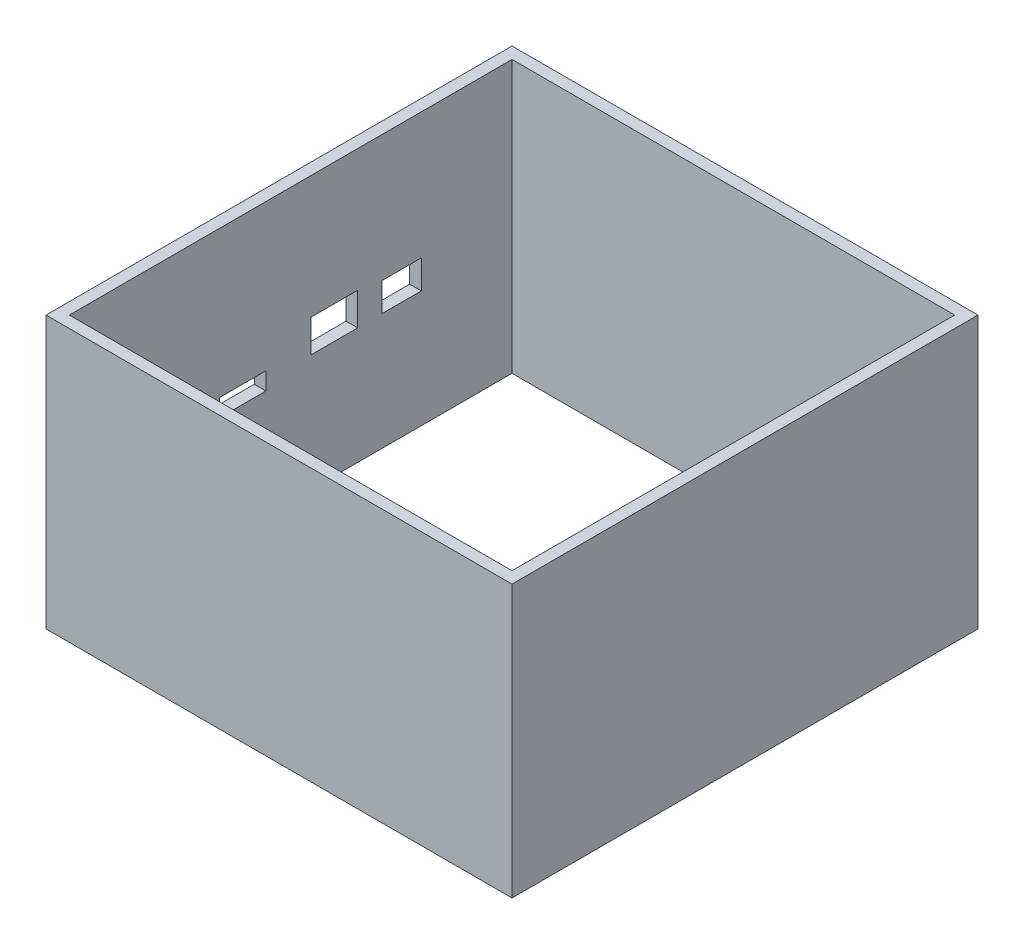
SolidWorks part; units mm, degrees
ref_plane "Front Plane" through (0, 0, 0) normal (0, 0, 1) x (1, 0, 0)
ref_plane "Top Plane" through (0, 0, 0) normal (0, 1, 0) x (1, 0, 0)
ref_plane "Right Plane" through (0, 0, 0) normal (1, 0, 0) x (0, 0, -1)
sketch "Sketch1" plane through (0, 0, 0) normal (0, 1, 0) x (1, 0, 0)
  line L1 (-70, -80) -> (70, -80)
  line L2 (-70, -80) -> (-70, 80)
  line L3 (-70, 80) -> (70, 80)
  line L4 (70, -80) -> (70, 80)
  line L5 (-70, -80) -> (70, 80) construction
  line L6 (-70, 80) -> (70, -80) construction
  point P0 (0, 0)
  dimension "D1" = 140
  dimension "D2" = 160
extrude "Boss-Extrude1" add sketch "Sketch1" along normal blind 3
sketch "Sketch2" plane through (0, 3, 0) normal (0, 1, 0) x (1, 0, 0)
  line L1 (-57, -57) -> (57, -57)
  line L2 (-57, -57) -> (-57, 57)
  line L3 (-57, 57) -> (57, 57)
  line L4 (57, -57) -> (57, 57)
  line L5 (-57, -57) -> (57, 57) construction
  line L6 (-57, 57) -> (57, -57) construction
  line L7 (60, -60) -> (-60, -60)
  line L8 (60, -60) -> (60, 60)
  line L9 (60, 60) -> (-60, 60)
  line L10 (-60, -60) -> (-60, 60)
  line L11 (60, -60) -> (-60, 60) construction
  line L12 (60, 60) -> (-60, -60) construction
  point P0 (0, 0)
  point P6 (0, 0)
  dimension "D1" = 114
  dimension "D2" = 114
  dimension "D3" = 120
extrude "Boss-Extrude2" add sketch "Sketch2" along normal blind 70
sketch "Sketch4" plane through (0, 73, 0) normal (0, 1, 0) x (1, 0, 0)
  line L1 (-60, 60) -> (60, 60)
  line L2 (-60, 60) -> (-60, -60)
  line L3 (-60, -60) -> (60, -60)
  line L4 (60, 60) -> (60, -60)
  dimension "D1" = 120
  dimension "D2" = 120
extrude "Boss-Extrude4" add sketch "Sketch4" along normal blind 3
sketch "Sketch5" plane through (0, 76, 0) normal (0, 1, 0) x (1, 0, 0)
  line L0 (-60, 60) -> (60, -60) construction
  line L1 (-10.27, -9.855) -> (29.63, -9.855)
  line L2 (-10.27, -9.855) -> (-10.27, 9.855)
  line L3 (-10.27, 9.855) -> (29.63, 9.855)
  line L4 (29.63, -9.855) -> (29.63, 9.855)
  line L5 (-10.27, -9.855) -> (29.63, 9.855) construction
  line L6 (-10.27, 9.855) -> (29.63, -9.855) construction
  line L7 (60, -60) -> (60, 60) construction
  line L8 (60, -60) -> (60, 60) construction
  line L9 (60, -60) -> (60, 60) construction
  line L10 (60, 60) -> (-60, 60) construction
  line L11 (60, 60) -> (-60, -60) construction
  circle A1 centre (34.39, -4.925) radius 2.1
  circle A2 centre (34.39, 4.925) radius 2.1
  circle A4 centre (-15.03, -4.925) radius 2.1
  circle A5 centre (-15.03, 4.925) radius 2.1
  point P3 (9.68, 0)
  dimension "D2" = 4.2
  dimension "D6" = 9.85
  dimension "D7" = 4.93
  dimension "D8" = 4.93
  dimension "D9" = 4.93
  dimension "D10" = 9.68
  dimension "D11" = 4.93
  dimension "D12" = 4.93
  dimension "D1" = 39.9
  dimension "D3" = 19.71
  dimension "D4" = 4.76
  dimension "D5" = 4.76
extrude "Cut-Extrude2" cut sketch "Sketch5" against normal blind 3
sketch "Sketch6" plane through (0, 76, 0) normal (0, 1, 0) x (1, 0, 0)
  line L1 (9.1491, -8.655) -> (-9.1491, -8.655)
  line L2 (9.1491, -8.655) -> (9.1491, 8.655)
  line L3 (9.1491, 8.655) -> (-9.1491, 8.655)
  line L4 (-9.1491, -8.655) -> (-9.1491, 8.655)
  line L5 (9.1491, -8.655) -> (-9.1491, 8.655) construction
  line L6 (9.1491, 8.655) -> (-9.1491, -8.655) construction
  point P0 (0, 0)
extrude "Cut-Extrude3" cut sketch "Sketch6" against normal blind 3
sketch "Sketch7" plane through (0, 0, 0) normal (0, 1, 0) x (1, 0, 0)
  line L1 (-45, -45) -> (45, -45)
  line L2 (-45, -45) -> (-45, 45)
  line L3 (-45, 45) -> (45, 45)
  line L4 (45, -45) -> (45, 45)
  line L5 (-45, -45) -> (45, 45) construction
  line L6 (-45, 45) -> (45, -45) construction
  point P0 (0, 0)
  dimension "D1" = 90
  dimension "D2" = 90
sketch "Sketch13" plane through (0, 76, 0) normal (0, 1, 0) x (1, 0, 0)
  arc A0 (-3.7926, 43.0768) -> (-0.8101, -42.9734) centre (-3.7926, 0) ccw construction
  arc A1 (-3.7926, 49.7288) -> (-0.3495, -49.6094) centre (-3.7926, 0) ccw
  arc A2 (-3.7926, 36.4249) -> (-1.2706, -36.3375) centre (-3.7926, 0) ccw
  arc A3 (-3.7926, 36.4249) -> (-3.7926, 49.7288) centre (-3.7926, 43.0768) ccw
  arc A4 (-0.3495, -49.6094) -> (-1.2706, -36.3375) centre (-0.8101, -42.9734) ccw
  point P3 (-46.8436, -1.4922)
extrude "Cut-Extrude8" cut sketch "Sketch13" against normal blind 5
sketch "Sketch15" plane through (0, 3, 0) normal (0, 1, 0) x (1, 0, 0)
  line L0 (70, 80) -> (-70, 80) construction
  line L1 (90, 80) -> (-169.0216, 80)
  line L2 (90, 80) -> (90, -100.2694)
  line L3 (90, -100.2694) -> (-169.0216, -100.2694)
  line L4 (-169.0216, 80) -> (-169.0216, -100.2694)
extrude "Boss-Extrude5" add sketch "Sketch15" against normal blind 3
sketch "Sketch18" plane through (0, 3, 0) normal (0, 1, 0) x (1, 0, 0)
  circle A0 centre (-55.452, -27.2274) radius 1.6 construction
  circle A1 centre (-55.452, -27.2274) radius 1.6
  circle A2 centre (-55.452, 32.2086) radius 1.6 construction
  circle A3 centre (-55.452, 32.2086) radius 1.6
  circle A4 centre (4.746, 32.2086) radius 1.6 construction
  circle A5 centre (4.746, 32.2086) radius 1.6
  circle A6 centre (4.746, -27.2274) radius 1.6 construction
  circle A7 centre (4.746, -27.2274) radius 1.6
extrude "Cut-Extrude9" cut sketch "Sketch18" against normal blind 10
sketch "Sketch19" plane through (-60, 0, 0) normal (-1, 0, 0) x (0, 0, 1)
  line L0 (12.3674, 3) -> (12.3674, 33) construction
  line L1 (-60, 3) -> (60, 3) construction
  line L2 (-5.6466, 31.35) -> (-5.6466, 26.9) construction
  line L3 (6.3674, 30.75) -> (18.3674, 30.75)
  line L4 (6.3674, 30.75) -> (6.3674, 35.25)
  line L5 (6.3674, 35.25) -> (18.3674, 35.25)
  line L6 (18.3674, 30.75) -> (18.3674, 35.25)
  line L7 (6.3674, 30.75) -> (18.3674, 35.25) construction
  line L8 (6.3674, 35.25) -> (18.3674, 30.75) construction
  line L9 (-5.2594, 33) -> (-5.2594, 41.4) construction
  line L10 (-5.2594, 33) -> (-17.2594, 33) construction
  line L11 (-5.2594, 41.4) -> (-17.2594, 41.4) construction
  line L12 (-17.2594, 33) -> (-17.2594, 41.4) construction
  line L13 (-33.6488, 33.0619) -> (-23.5648, 33.0619) construction
  line L14 (-28.1126, 38.85) -> (-28.1126, 27.45) construction
  line L15 (-23.5648, 40.424) -> (-23.5648, 33.0619) construction
  line L16 (-33.6488, 40.424) -> (-23.5648, 40.424) construction
  line L17 (-33.6488, 40.424) -> (-33.6488, 33.0619) construction
  line L18 (-5.2594, 33) -> (-5.2594, 41.4)
  line L19 (-5.2594, 33) -> (-17.2594, 33)
  line L20 (-5.2594, 41.4) -> (-17.2594, 41.4)
  line L21 (-17.2594, 33) -> (-17.2594, 41.4)
  line L22 (-33.6488, 33.0619) -> (-23.5648, 33.0619)
  line L23 (-28.1126, 38.85) -> (-28.1126, 27.45)
  line L24 (-23.5648, 40.424) -> (-23.5648, 33.0619)
  line L25 (-33.6488, 40.424) -> (-23.5648, 40.424)
  line L26 (-33.6488, 40.424) -> (-33.6488, 33.0619)
  dimension "D1" = 14.86
  dimension "D2" = 30
  dimension "D3" = 4.5
  dimension "D4" = 90
  dimension "D5" = 12
extrude "Cut-Extrude11" cut sketch "Sketch19" against normal blind 5
sketch "Sketch20" plane through (0, 0, 60) normal (0, 0, 1) x (1, 0, 0)
  line L0 (60, 76) -> (60, 3) construction
  line L1 (-169.0216, 3) -> (94.8999, 3)
  line L2 (-169.0216, 3) -> (-169.0216, -16.6306)
  line L3 (-169.0216, -16.6306) -> (94.8999, -16.6306)
  line L4 (94.8999, 3) -> (94.8999, -16.6306)
  line L5 (-60, 76) -> (60, 76)
  line L6 (-60, 76) -> (-60, 73)
  line L7 (-60, 73) -> (60, 73)
  line L8 (60, 76) -> (60, 73)
  dimension "D1" = 3
extrude "Cut-Extrude12" cut sketch "Sketch20" against normal through all
sketch "Sketch21" plane through (0, 3, 0) normal (0, 1, 0) x (1, 0, 0)
  line L1 (-169.0216, -60) -> (90, -60)
  line L2 (-169.0216, -60) -> (-169.0216, -100.2694)
  line L3 (-169.0216, -100.2694) -> (90, -100.2694)
  line L4 (90, -60) -> (90, -100.2694)
extrude "Cut-Extrude13" cut sketch "Sketch21" against normal through all
